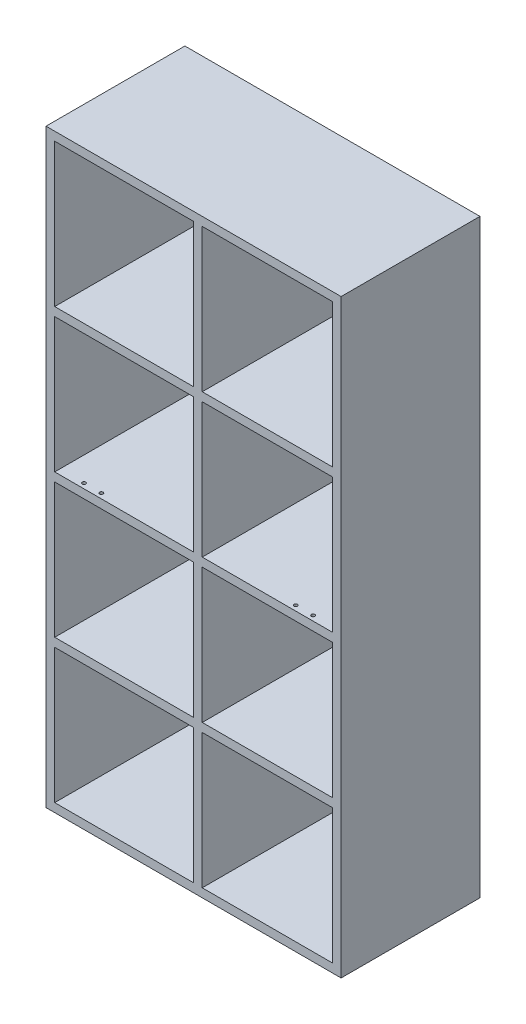
SolidWorks part; units mm, degrees
ref_plane "Płaszczyzna przednia" through (0, 0, 0) normal (0, 0, 1) x (1, 0, 0)
ref_plane "Płaszczyzna górna" through (0, 0, 0) normal (0, 1, 0) x (1, 0, 0)
ref_plane "Płaszczyzna prawa" through (0, 0, 0) normal (1, 0, 0) x (0, 0, -1)
sketch "Szkic1" plane through (0, 0, 0) normal (0, 0, 1) x (1, 0, 0)
  line L0 (0, 0) -> (800, 0)
  line L1 (0, 0) -> (0, 1650)
  line L2 (0, 412.5) -> (800, 412.5)
  line L4 (400, 0) -> (400, 1650)
  line L5 (800, 0) -> (800, 1650)
  line L6 (0, 825) -> (800, 825)
  line L7 (0, 1237.5) -> (800, 1237.5)
  line L8 (0, 1650) -> (800, 1650)
  line L42 (370, 382.5) -> (370, 795) construction
  dimension "D1" = 1650
  dimension "D2" = 800
  dimension "D3" = 3
  dimension "D4" = 5
extrude "Wyciągnięcie-cienka ścianka1" add sketch "Szkic1" along normal blind 400 thin contours L7 | L5 L8 L1 L0 | L4 | L6 | L2
ref_plane "Płaszczyzna1" through (0, 825, 0) normal (0, 1, 0) x (1, 0, 0)
sketch "Szkic2" plane through (0, 825, 0) normal (0, 1, 0) x (1, 0, 0)
  circle A0 centre (70, -385.65) radius 5
  circle A1 centre (120, -385.65) radius 5
  dimension "D1" = 10
  dimension "D2" = 10
  dimension "D3" = 50
  dimension "D4" = 14.35
  dimension "D5" = 14.35
  dimension "D6" = 70
extrude "Wytnij-wyciągnięcie1" cut sketch "Szkic2" against normal blind 25
sketch "Szkic4" plane through (0, 825, 0) normal (0, 1, 0) x (1, 0, 0)
  circle A0 centre (730, -385.65) radius 5
  circle A1 centre (680, -385.65) radius 5
  dimension "D1" = 10
  dimension "D2" = 10
  dimension "D3" = 50
  dimension "D4" = 70
  dimension "D5" = 14.35
  dimension "D6" = 14.35
extrude "Wytnij-wyciągnięcie2" cut sketch "Szkic4" against normal blind 25
ref_plane "Płaszczyzna2" through (0, 0, 400) normal (0, 0, 1) x (1, 0, 0)
sketch "Szkic5" plane through (0, 0, 400) normal (0, 0, 1) x (1, 0, 0)
  line L0 (0, 825) -> (800, 825)
sketch "Szkic6" plane through (-25, 0, 0) normal (-1, 0, 0) x (0, 0, 1)
  line L0 (72.0017, 1675) -> (72.0017, 1663) construction
  line L1 (400, 1675) -> (0, 1675) construction
  line L2 (152.8117, 1675) -> (152.8117, 1663) construction
  line L3 (0, -25) -> (0, 1675) construction
  line L4 (400, -25) -> (0, -25) construction
  circle A0 centre (72.0017, 1663) radius 5
  circle A1 centre (152.8117, 1663) radius 5
  dimension "D3" = 10
  dimension "D4" = 10
  dimension "D1" = 80.81
  dimension "D2" = 12
  dimension "D5" = 72.0017
  dimension "D6" = 400
extrude "Wytnij-wyciągnięcie3" cut sketch "Szkic6" against normal blind 40
equation "\"Wyciągnięcie-cienka ścianka1\"= IIF ( \"D1@Szkic1\" < 1650 , \"suppressed\" , \"unsuppressed\" )"
equation "\"D4@Szkic1\"= \"D1@Szkic1\" / 330"
equation "\"D3@Szkic1\"= \"D2@Szkic1\" / 300"
